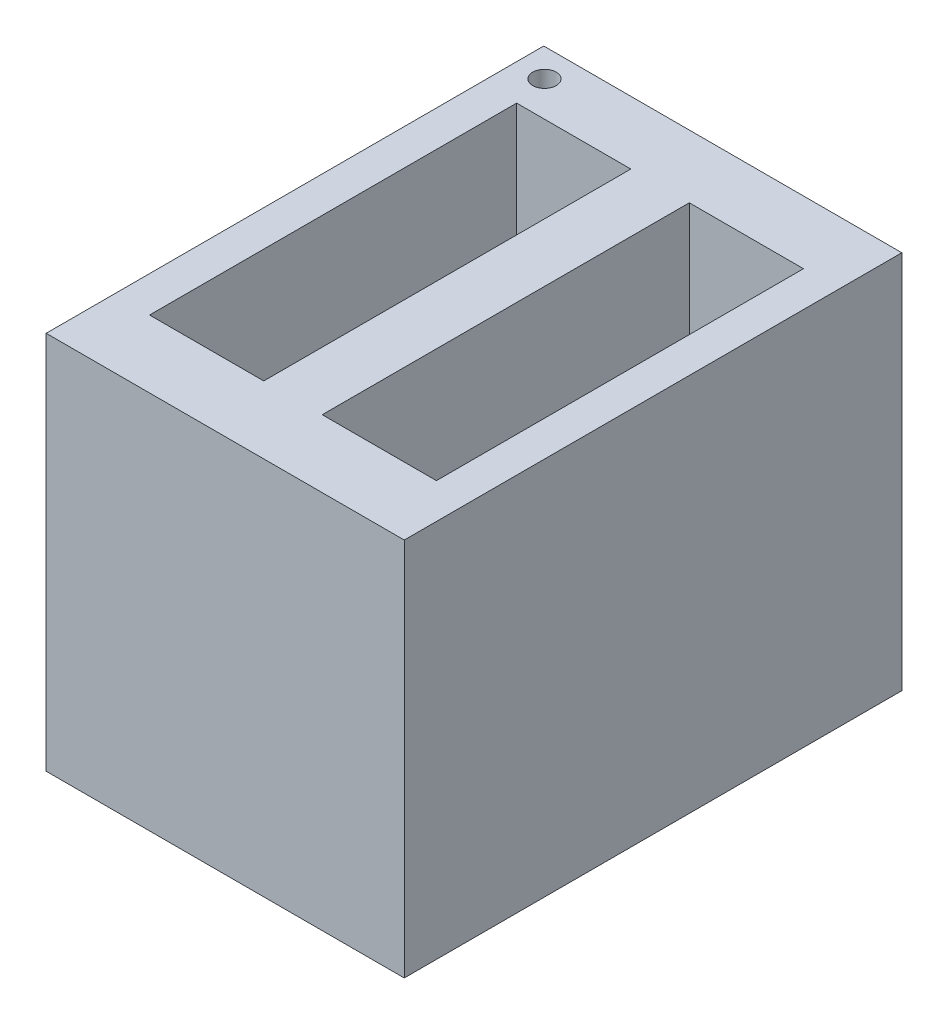
SolidWorks part; units mm, degrees
ref_plane "Alzado" through (0, 0, 0) normal (0, 0, 1) x (1, 0, 0)
ref_plane "Planta" through (0, 0, 0) normal (0, 1, 0) x (1, 0, 0)
ref_plane "Vista lateral" through (0, 0, 0) normal (1, 0, 0) x (0, 0, -1)
sketch "Croquis1" plane through (0, 0, 0) normal (0, 1, 0) x (1, 0, 0)
  line L1 (0, 0) -> (4.39, 0)
  line L2 (0, 0) -> (0, 6.1)
  line L3 (0, 6.1) -> (4.39, 6.1)
  line L4 (4.39, 0) -> (4.39, 6.1)
extrude "Saliente-Extruir1" add sketch "Croquis1" along normal blind 4.65
sketch "Croquis3" plane through (0, 4.65, 0) normal (0, 1, 0) x (1, 0, 0)
  line L0 (2.195, 0) -> (2.195, 3.0776) construction
  line L1 (0, 0) -> (4.39, 0) construction
  line L2 (2.195, 3.0776) -> (1.14, 3.0776) construction
  line L3 (2.195, 3.0776) -> (3.2568, 3.0776) construction
  line L5 (1.84, 0.8276) -> (0.44, 0.8276)
  line L6 (1.84, 0.8276) -> (1.84, 5.3276)
  line L7 (1.84, 5.3276) -> (0.44, 5.3276)
  line L8 (0.44, 0.8276) -> (0.44, 5.3276)
  line L9 (1.84, 0.8276) -> (0.44, 5.3276) construction
  line L10 (1.84, 5.3276) -> (0.44, 0.8276) construction
  line L11 (2.5568, 0.8276) -> (3.9568, 0.8276)
  line L12 (2.5568, 0.8276) -> (2.5568, 5.3276)
  line L13 (2.5568, 5.3276) -> (3.9568, 5.3276)
  line L14 (3.9568, 0.8276) -> (3.9568, 5.3276)
  line L15 (2.5568, 0.8276) -> (3.9568, 5.3276) construction
  line L16 (2.5568, 5.3276) -> (3.9568, 0.8276) construction
extrude "Cortar-Extruir1" cut sketch "Croquis3" against normal through all
sketch "Croquis4" plane through (0, 4.65, 0) normal (0, 1, 0) x (1, 0, 0)
  circle A0 centre (0.3534, 5.7557) radius 0.1438
extrude "Cortar-Extruir2" cut sketch "Croquis4" against normal blind 0.25
sketch "Croquis5" plane through (0, 0, 0) normal (-1, 0, 0) x (0, 0, 1)
  text T0 "QRD1114\r\nFC20" font "Century Gothic" height 1.2
